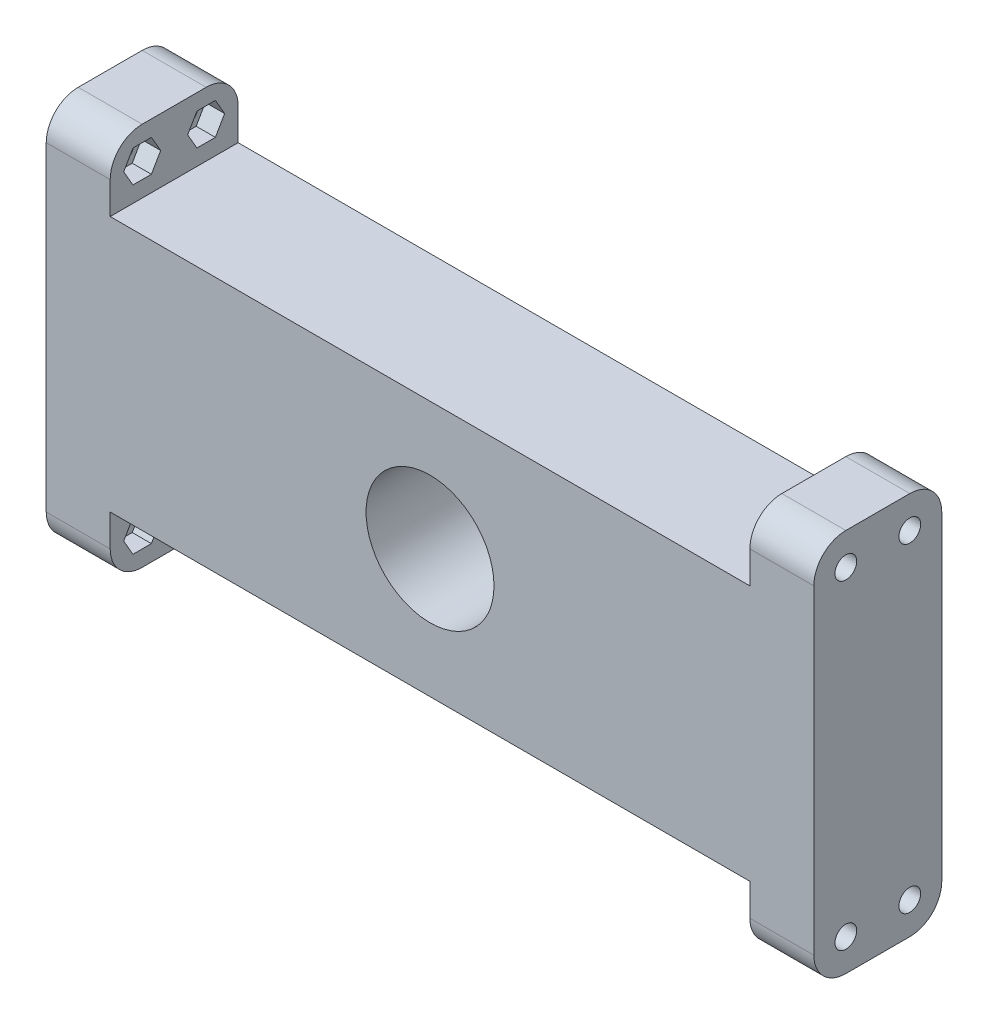
SolidWorks part; units mm, degrees
material "ESUN PLA +"
ref_plane "Front Plane" through (0, 0, 0) normal (0, 0, 1) x (1, 0, 0)
ref_plane "Top Plane" through (0, 0, 0) normal (0, 1, 0) x (1, 0, 0)
ref_plane "Right Plane" through (0, 0, 0) normal (1, 0, 0) x (0, 0, -1)
sketch "Sketch1" plane through (0, 0, 0) normal (0, 0, 1) x (1, 0, 0)
  line L1 (-60, -30) -> (60, -30)
  line L2 (-60, -30) -> (-60, 30)
  line L3 (-60, 30) -> (60, 30)
  line L4 (60, -30) -> (60, 30)
  line L5 (-60, -30) -> (60, 30) construction
  line L6 (-60, 30) -> (60, -30) construction
  point P0 (0, 0)
  dimension "D1" = 120
  dimension "D2" = 60
extrude "Boss-Extrude1" add sketch "Sketch1" along normal mid plane 20
sketch "Sketch2" plane through (0, 0, 10) normal (0, 0, 1) x (1, 0, 0)
  line L0 (-60, -30) -> (60, -30) construction
  line L1 (-50, -30) -> (50, -30)
  line L2 (-50, -30) -> (-50, -20)
  line L3 (-50, -20) -> (50, -20)
  line L4 (50, -30) -> (50, -20)
  line L5 (60, 30) -> (-60, 30) construction
  line L6 (50, 30) -> (-50, 30)
  line L7 (50, 30) -> (50, 20)
  line L8 (50, 20) -> (-50, 20)
  line L9 (-50, 30) -> (-50, 20)
  line L11 (-60, 30) -> (-60, -30) construction
  line L12 (60, -30) -> (60, 30) construction
  dimension "D1" = 10
  dimension "D2" = 10
  dimension "D3" = 10
extrude "Cut-Extrude1" cut sketch "Sketch2" against normal through all both and the other way through all
fillet "Fillet1" radius 5 8 edges at (55, 30, -10) (55, 30, 10) (55, -30, 10) (55, -30, -10) (-55, -30, -10) (-55, -30, 10) (-55, 30, -10) (-55, 30, 10)
sketch "Sketch4" plane through (50, 0, 0) normal (-1, 0, 0) x (0, 0, 1)
  line L0 (-10, 20) -> (-10, 25) construction
  line L1 (-5, 30) -> (5, 30) construction
  circle A0 centre (-5, 25) radius 1.7
  dimension "D1" = 5
  dimension "D3" = 3.4
  dimension "D2" = 5
extrude "Cut-Extrude3" cut sketch "Sketch4" against normal through all both and the other way through all
sketch "Sketch5" plane through (50, 0, 0) normal (-1, 0, 0) x (0, 0, 1)
  line L1 (-7.8868, 25) -> (-6.4434, 22.5)
  line L2 (-6.4434, 22.5) -> (-3.5566, 22.5)
  line L3 (-3.5566, 22.5) -> (-2.1132, 25)
  line L4 (-2.1132, 25) -> (-3.5566, 27.5)
  line L5 (-3.5566, 27.5) -> (-6.4434, 27.5)
  line L6 (-6.4434, 27.5) -> (-7.8868, 25)
  circle A0 centre (-5, 25) radius 2.5 construction
  circle A1 centre (-5, 25) radius 1.7 construction
  dimension "D1" = 5
extrude "Cut-Extrude4" cut sketch "Sketch5" against normal blind 3
mirror "Mirror1" about plane through (0, 0, 0) normal (1, 0, 0) of "Cut-Extrude4", "Cut-Extrude3" second plane through (0, 0, 0) second plane normal (0, 0, 1)
mirror "Mirror2" about plane through (0, 0, 0) normal (0, 1, 0) of "Mirror1", "Cut-Extrude4"
sketch "Sketch6" plane through (0, 0, 10) normal (0, 0, 1) x (1, 0, 0)
  circle A0 centre (0, 0) radius 10
  dimension "D1" = 20
extrude "Cut-Extrude5" cut sketch "Sketch6" against normal through all
